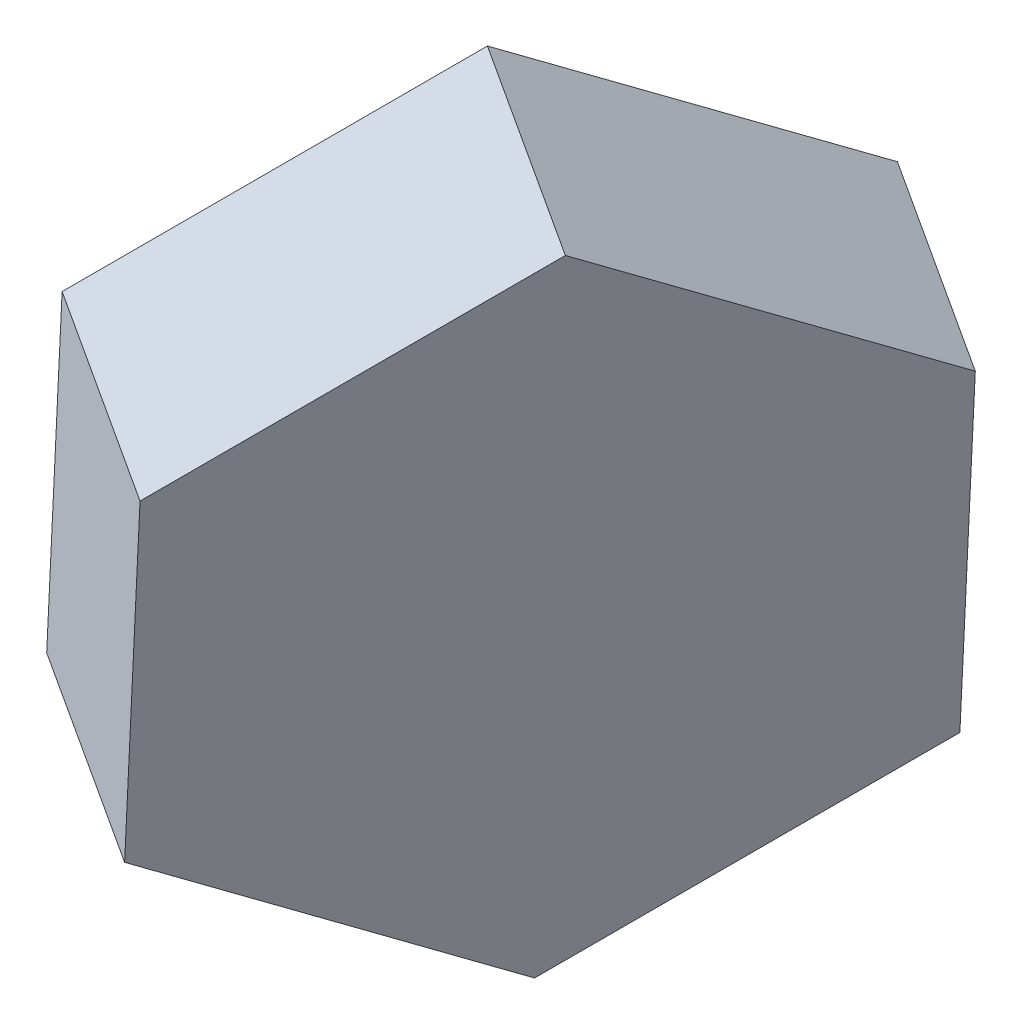
SolidWorks part; units mm, degrees
ref_plane "前视基准面" through (0, 0, 0) normal (0, 0, 1) x (1, 0, 0)
ref_plane "上视基准面" through (0, 0, 0) normal (0, 1, 0) x (1, 0, 0)
ref_plane "右视基准面" through (0, 0, 0) normal (1, 0, 0) x (0, 0, -1)
sketch "草图1" plane through (0, 0, 0) normal (0, 0, 1) x (1, 0, 0)
  line L1 (7.9947, 13.8472) -> (-7.9947, 13.8472)
  line L2 (-7.9947, 13.8472) -> (-15.9894, 0)
  line L3 (-15.9894, 0) -> (-7.9947, -13.8472)
  line L4 (-7.9947, -13.8472) -> (7.9947, -13.8472)
  line L5 (7.9947, -13.8472) -> (15.9894, 0)
  line L6 (15.9894, 0) -> (7.9947, 13.8472)
  circle A0 centre (0, 0) radius 13.8472 construction
extrude "凸台-拉伸1" add sketch "草图1" along normal blind 10
move or copy body "实体-移动/复制1" bodies to move or copy 106 copy no rotation origin (-0.6387, -1.542, 4.3613) rotation axis (0.3574, 0.8629, 0.3574) rotation angle 64.737
ref_plane "基准面1" through (-2.1339, 0.3661, -1.25) normal (-0.8536, 0.1464, -0.5) x (-0.4928, 0.0846, 0.866)
sketch "草图2" plane through (-2.1339, 0.3661, -1.25) normal (-0.8536, 0.1464, -0.5) x (-0.4928, 0.0846, 0.866)
  line L0 (5.7972, 15.9219) -> (2.8631, -15.9219) construction
  circle A0 centre (4.3301, 0) radius 4
  dimension "D1" = 8
extrude "凸台-拉伸2" add sketch "草图2" along normal blind 3
sketch "草图3" plane through (0, 0, 0) normal (0, 0, 1) x (1, 0, 0)
  line L0 (221.075, -80.7953) -> (193.2392, 26.4059)
  line L1 (193.2392, 26.4059) -> (97.5388, 41.5241)
sketch "草图4" plane through (0, 0, 0) normal (0, 0, 1) x (1, 0, 0)
  line L0 (130.6206, -164.6518) -> (8.6354, -82.8962)
  circle A0 centre (-30.785, -123.774) radius 33.5791
